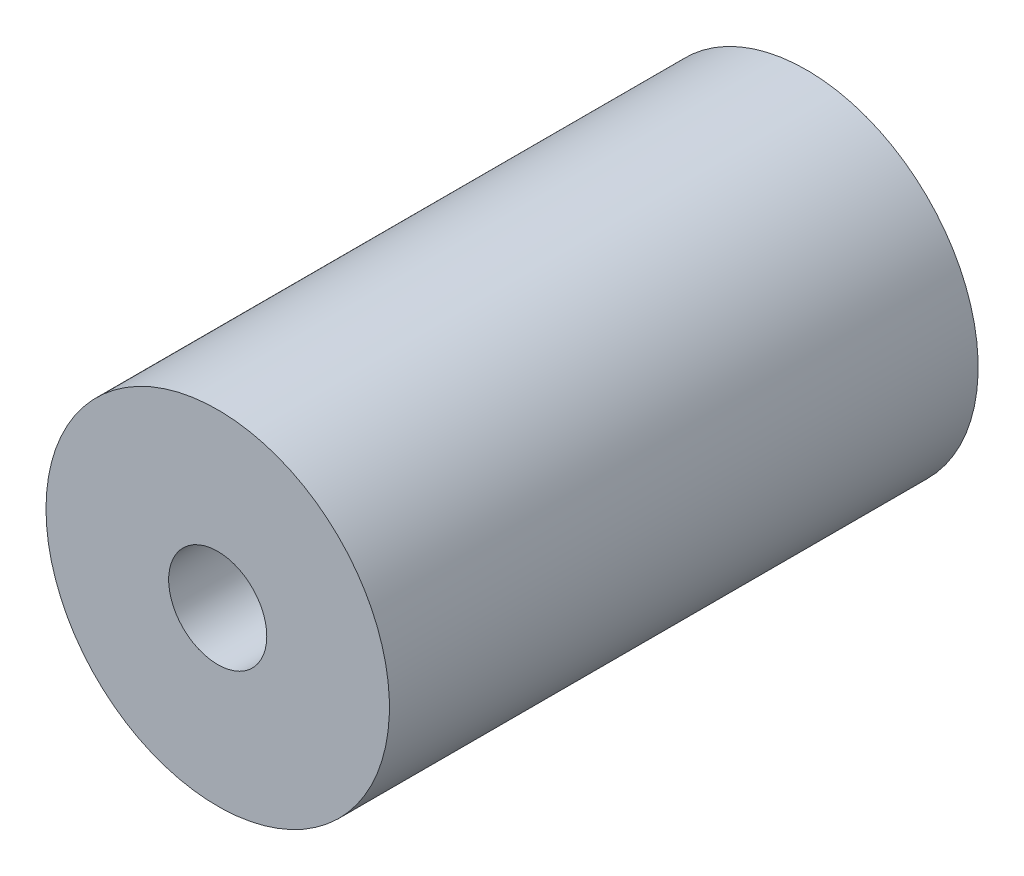
SolidWorks part; units mm, degrees
ref_plane "Front Plane" through (0, 0, 0) normal (0, 0, 1) x (1, 0, 0)
ref_plane "Top Plane" through (0, 0, 0) normal (0, 1, 0) x (1, 0, 0)
ref_plane "Right Plane" through (0, 0, 0) normal (1, 0, 0) x (0, 0, -1)
sketch "Sketch1" plane through (0, 0, 0) normal (0, 0, 1) x (1, 0, 0)
  circle A0 centre (0, 0) radius 4.445
  dimension "D1" = 8.89
extrude "Boss-Extrude1" add sketch "Sketch1" along normal blind 15.24
sketch "Sketch2" plane through (0, 0, 15.24) normal (0, 0, 1) x (1, 0, 0)
  circle A0 centre (0, 0) radius 1.27
  dimension "D1" = 2.54
extrude "Cut-Extrude1" cut sketch "Sketch2" against normal blind 2.54
